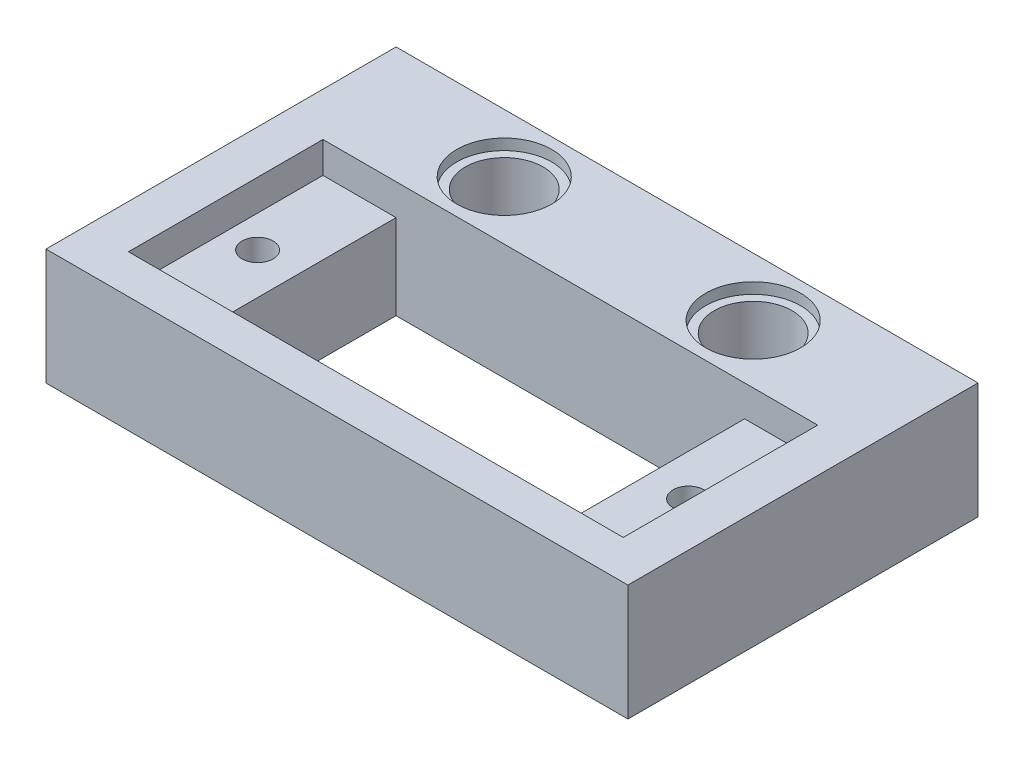
SolidWorks part; units mm, degrees
ref_plane "Front Plane" through (0, 0, 0) normal (0, 0, 1) x (1, 0, 0)
ref_plane "Top Plane" through (0, 0, 0) normal (0, 1, 0) x (1, 0, 0)
ref_plane "Right Plane" through (0, 0, 0) normal (1, 0, 0) x (0, 0, -1)
sketch "Sketch1" plane through (0, 0, 0) normal (0, 1, 0) x (1, 0, 0)
  line L0 (0, 14.5365) -> (0, -17.0646) construction
  line L1 (-33.4738, 0) -> (30.103, 0) construction
  line L2 (-18.7, 13.75) -> (-18.7, -8.75)
  line L3 (-11.2, 6.25) -> (11.2, 6.25)
  line L4 (-11.2, 6.25) -> (-11.2, -6.25)
  line L5 (-11.2, -6.25) -> (11.2, -6.25)
  line L6 (11.2, 6.25) -> (11.2, -6.25)
  line L7 (-11.2, 6.25) -> (11.2, -6.25) construction
  line L8 (-11.2, -6.25) -> (11.2, 6.25) construction
  line L9 (-18.7, -8.75) -> (18.7, -8.75)
  line L10 (18.7, -8.75) -> (18.7, 13.75)
  line L11 (18.7, 13.75) -> (-18.7, 13.75)
  circle A0 centre (13.85, 0) radius 1
  circle A1 centre (-13.85, 0) radius 1
  point P5 (0, 0)
  point P18 (18.7, 2.5)
  dimension "D3" = 2
  dimension "D1" = 12.5
  dimension "D2" = 22.4
  dimension "D4" = 27.7
  dimension "D5" = 7.5
  dimension "D6" = 7.5
  dimension "D7" = 7.5
  dimension "D8" = 2.5
extrude "Boss-Extrude1" add sketch "Sketch1" against normal blind 7.46
sketch "Sketch2" plane through (0, 0, 0) normal (0, 1, 0) x (1, 0, 0)
  line L0 (0, 6.25) -> (0, -6.25) construction
  line L1 (11.2, 6.25) -> (-11.2, 6.25) construction
  line L2 (-11.2, -6.25) -> (11.2, -6.25) construction
  line L3 (-18.7, 0) -> (18.7, 0) construction
  line L4 (-18.7, 13.75) -> (-18.7, -8.75) construction
  line L5 (18.7, -8.75) -> (18.7, 13.75) construction
  line L7 (-15.9, 6.25) -> (15.9, 6.25)
  line L8 (-15.9, 6.25) -> (-15.9, -6.25)
  line L9 (-15.9, -6.25) -> (15.9, -6.25)
  line L10 (15.9, 6.25) -> (15.9, -6.25)
  line L11 (-15.9, 6.25) -> (15.9, -6.25) construction
  line L12 (-15.9, -6.25) -> (15.9, 6.25) construction
  point P13 (0, 0)
  dimension "D1" = 12.5
  dimension "D2" = 31.8
extrude "Cut-Extrude1" cut sketch "Sketch2" against normal blind 2
sketch "Sketch3" plane through (0, 0, 0) normal (0, 1, 0) x (1, 0, 0)
  line L0 (0, 6.25) -> (0, 13.75) construction
  line L1 (15.9, 6.25) -> (-15.9, 6.25) construction
  line L2 (18.7, 13.75) -> (-18.7, 13.75) construction
  line L3 (0, 10) -> (18.7, 10) construction
  line L4 (18.7, -8.75) -> (18.7, 13.75) construction
  circle A0 centre (8, 10) radius 2.5
  circle A1 centre (-8, 10) radius 2.5
  dimension "D1" = 5
  dimension "D2" = 8
extrude "Cut-Extrude2" cut sketch "Sketch3" against normal through all
sketch "Sketch4" plane through (0, 0, 0) normal (0, 1, 0) x (1, 0, 0)
  circle A0 centre (-8, 10) radius 3.05
  circle A1 centre (8, 10) radius 3.05
  dimension "D1" = 6.1
  dimension "D2" = 6.1
extrude "Cut-Extrude3" cut sketch "Sketch4" against normal blind 0.7
sketch "Sketch5" plane through (0, -7.46, 0) normal (0, -1, 0) x (-1, 0, 0)
  circle A0 centre (-8, 10) radius 3.05
  circle A1 centre (8, 10) radius 3.05
  dimension "D1" = 6.1
  dimension "D2" = 6.1
extrude "Cut-Extrude4" cut sketch "Sketch5" against normal blind 0.7
sketch3d "URDF Reference"
  line L0 (0, 0, 0) -> (10, 0, 0) construction
  line L1 (0, 0, 0) -> (0, 0, -10) construction
  point P0 (0, 0, 0)
  point P1 (0, 0, 0)
